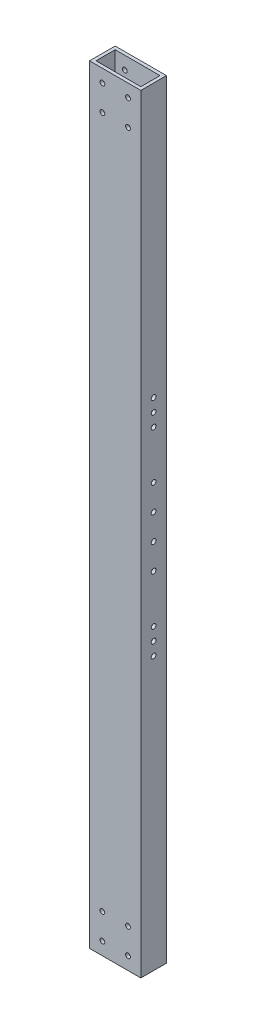
SolidWorks part; units mm, degrees
ref_plane "Front Plane" through (0, 0, 0) normal (0, 0, 1) x (1, 0, 0)
ref_plane "Top Plane" through (0, 0, 0) normal (0, 1, 0) x (1, 0, 0)
ref_plane "Right Plane" through (0, 0, 0) normal (1, 0, 0) x (0, 0, -1)
sketch "Sketch1" plane through (0, 0, 0) normal (0, 1, 0) x (1, 0, 0)
  line L1 (25.4, 12.7) -> (-25.4, 12.7)
  line L2 (25.4, 12.7) -> (25.4, -12.7)
  line L3 (25.4, -12.7) -> (-25.4, -12.7)
  line L4 (-25.4, 12.7) -> (-25.4, -12.7)
  line L5 (0, -12.7) -> (0, 12.7) construction
  line L6 (25.4, 0) -> (-25.4, 0) construction
  point P0 (0, 0)
  dimension "D1" = 50.8
  dimension "D2" = 25.4
extrude "Boss-Extrude1" add sketch "Sketch1" along normal mid plane 762
shell "Shell1" thickness 3.175
sketch "Sketch4" plane through (25.4, 0, 0) normal (1, 0, 0) x (0, 0, -1)
  line L0 (0, 0) -> (0, 50000) construction
  line L2 (0, 85.5345) -> (0, 110.9345) construction
  line L3 (0, 0) -> (50000, 0) construction
  line L4 (8.3008, 76.2) -> (-8.3008, 76.2) construction
  line L5 (8.3008, 76.2) -> (8.3008, 120.269) construction
  line L6 (8.3008, 120.269) -> (-8.3008, 120.269) construction
  line L7 (-8.3008, 76.2) -> (-8.3008, 120.269) construction
  line L8 (0, 120.269) -> (0, 76.2) construction
  line L9 (8.3008, 98.2345) -> (-8.3008, 98.2345) construction
  line L10 (8.3008, -98.2345) -> (-8.3008, -98.2345) construction
  line L11 (0, -120.269) -> (0, -76.2) construction
  line L12 (-8.3008, -76.2) -> (-8.3008, -120.269) construction
  line L13 (8.3008, -120.269) -> (-8.3008, -120.269) construction
  line L14 (8.3008, -76.2) -> (8.3008, -120.269) construction
  line L15 (8.3008, -76.2) -> (-8.3008, -76.2) construction
  line L16 (0, -85.5345) -> (0, -110.9345) construction
  circle A0 centre (0, 110.9345) radius 2.3812
  circle A1 centre (0, 98.2345) radius 2.3812
  circle A4 centre (0, 85.5345) radius 2.3812
  circle A5 centre (0, -85.5345) radius 2.3812
  circle A6 centre (0, -98.2345) radius 2.3812
  circle A7 centre (0, -110.9345) radius 2.3812
  circle A8 centre (0, -12.7) radius 2.3813
  circle A9 centre (0, -38.1) radius 2.3812
  circle A10 centre (0, 38.1) radius 2.3812
  circle A11 centre (0, 12.7) radius 2.3813
  point P15 (0, 98.2345)
  point P29 (0, -98.2345)
  dimension "D5" = 25.4
  dimension "D1" = 4.7625
  dimension "D6" = 4.7625
  dimension "D2" = 12.7
  dimension "D3" = 44.069
  dimension "D4" = 76.2
  dimension "D7" = 25.4
extrude "Cut-Extrude1" cut sketch "Sketch4" against normal through all
sketch "Sketch5" plane through (0, 0, 12.7) normal (0, 0, 1) x (1, 0, 0)
  line L0 (-25.4, 381) -> (25.4, 381) construction
  line L1 (12.7, 368.3) -> (-12.7, 368.3) construction
  line L2 (12.7, 368.3) -> (12.7, 342.9) construction
  line L3 (12.7, 342.9) -> (-12.7, 342.9) construction
  line L4 (-12.7, 368.3) -> (-12.7, 342.9) construction
  line L5 (0, 342.9) -> (0, 368.3) construction
  line L6 (12.7, 355.6) -> (-12.7, 355.6) construction
  line L7 (0, 0) -> (50000, 0) construction
  line L8 (12.7, -355.6) -> (-12.7, -355.6) construction
  line L9 (0, -342.9) -> (0, -368.3) construction
  line L10 (-12.7, -368.3) -> (-12.7, -342.9) construction
  line L11 (12.7, -342.9) -> (-12.7, -342.9) construction
  line L12 (12.7, -368.3) -> (12.7, -342.9) construction
  line L13 (12.7, -368.3) -> (-12.7, -368.3) construction
  circle A0 centre (-12.7, 368.3) radius 2.3813
  circle A1 centre (12.7, 368.3) radius 2.3813
  circle A2 centre (12.7, 342.9) radius 2.3813
  circle A3 centre (-12.7, 342.9) radius 2.3813
  circle A4 centre (-12.7, -342.9) radius 2.3813
  circle A5 centre (12.7, -342.9) radius 2.3813
  circle A6 centre (12.7, -368.3) radius 2.3813
  circle A7 centre (-12.7, -368.3) radius 2.3813
  point P8 (0, 355.6)
  point P27 (0, -355.6)
  dimension "D1" = 4.7625
  dimension "D2" = 25.4
  dimension "D3" = 12.7
extrude "Cut-Extrude2" cut sketch "Sketch5" against normal through all both
